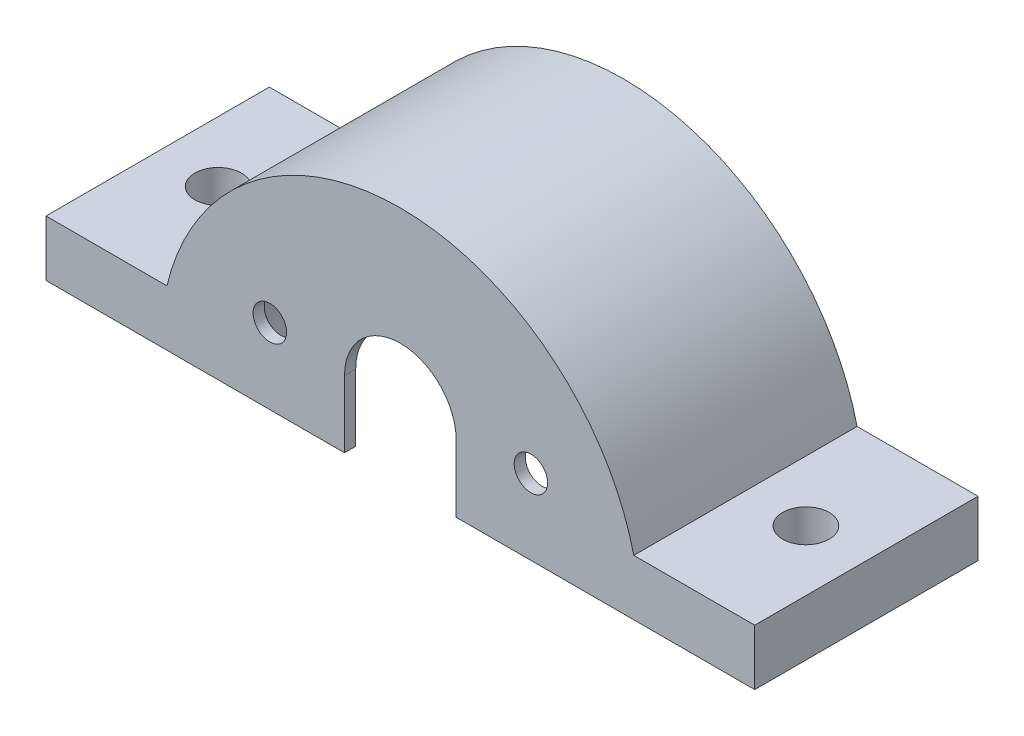
SolidWorks part; units mm, degrees
ref_plane "Front Plane" through (0, 0, 0) normal (0, 0, 1) x (1, 0, 0)
ref_plane "Top Plane" through (0, 0, 0) normal (0, 1, 0) x (1, 0, 0)
ref_plane "Right Plane" through (0, 0, 0) normal (1, 0, 0) x (0, 0, -1)
sketch "Sketch1" plane through (0, 0, 0) normal (0, 0, 1) x (1, 0, 0)
  line L0 (-16.5, 0) -> (-31.74, 0)
  line L1 (-31.74, 0) -> (-31.74, 5)
  line L2 (-31.74, 5) -> (-20.9105, 5)
  line L8 (0, 0) -> (0, 50000) construction
  line L9 (16.5, 0) -> (31.74, 0)
  line L10 (31.74, 0) -> (31.74, 5)
  line L11 (31.74, 5) -> (20.9105, 5)
  circle A8 centre (0, 0) radius 16.5 construction
  arc A9 (-16.5, 0) -> (16.5, 0) centre (0, 0) cw
  arc A10 (-20.9105, 5) -> (20.9105, 5) centre (0, 0) cw
  dimension "D1" = 33
  dimension "D2" = 21.5
  dimension "D4" = 15.24
  dimension "D3" = 5
extrude "Boss-Extrude1" add sketch "Sketch1" along normal blind 20
sketch "Sketch2" plane through (0, 0, 20) normal (0, 0, 1) x (1, 0, 0)
  line L0 (5, 0) -> (16.5, 0)
  line L3 (0, 0) -> (0, 50000) construction
  line L4 (-5, 0) -> (-5, 6)
  line L6 (-5, 0) -> (-16.5, 0)
  line L7 (5, 0) -> (5, 6)
  arc A0 (-16.5, 0) -> (16.5, 0) centre (0, 0) cw
  arc A3 (5, 6) -> (-5, 6) centre (0, 6) ccw
  dimension "D2" = 5
  dimension "D1" = 6
extrude "Boss-Extrude2" add sketch "Sketch2" against normal blind 1
sketch "Sketch3" plane through (0, 0, 20) normal (0, 0, 1) x (1, 0, 0)
  line L0 (0, 0) -> (0, -13.5) construction
  line L1 (0, 0) -> (-11.6913, 6.75) construction
  circle A0 centre (0, 0) radius 21.5 construction
  circle A1 centre (0, 0) radius 13.5 construction
  circle A2 centre (0, -13.5) radius 1.5 construction
  circle A3 centre (-11.6913, 6.75) radius 1.5 construction
  circle A4 centre (11.6913, 6.75) radius 1.5 construction
  circle A5 centre (-11.6913, 6.75) radius 1.5
  circle A6 centre (11.6913, 6.75) radius 1.5
  dimension "D1" = 27
  dimension "D2" = 43
  dimension "D3" = 3
  dimension "D5" = 120
  dimension "D6" = 13.5
  dimension "D4" = 3
extrude "Cut-Extrude1" cut sketch "Sketch3" against normal through all
sketch "Sketch4" plane through (0, 5, 0) normal (0, 1, 0) x (1, 0, 0)
  line L0 (26.3253, 0) -> (26.3253, 50000) construction
  line L1 (31.74, 0) -> (20.9105, 0) construction
  line L2 (31.74, -10) -> (50031.74, -10) construction
  line L3 (31.74, -20) -> (31.74, 0) construction
  line L4 (0, 0) -> (0, 50000) construction
  line L5 (20.9105, 0) -> (-20.9105, 0) construction
  circle A0 centre (26.3253, -10) radius 2.0828
  circle A1 centre (-26.3253, -10) radius 2.0828
  point P4 (26.3253, 0)
  point P9 (31.74, -10)
  point P16 (0, 0)
  dimension "D1" = 4.1656
extrude "Cut-Extrude2" cut sketch "Sketch4" against normal through all
